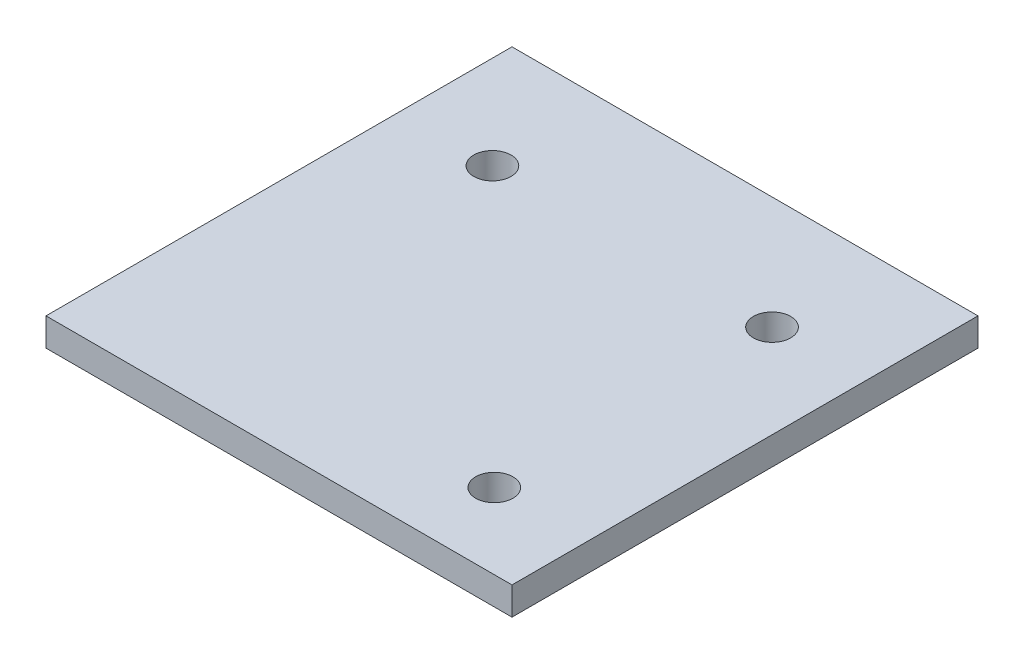
SolidWorks part; units mm, degrees
ref_plane "前视基准面" through (0, 0, 0) normal (0, 0, 1) x (1, 0, 0)
ref_plane "上视基准面" through (0, 0, 0) normal (0, 1, 0) x (1, 0, 0)
ref_plane "右视基准面" through (0, 0, 0) normal (1, 0, 0) x (0, 0, -1)
sketch "草图1" plane through (0, 0, 0) normal (0, 1, 0) x (1, 0, 0)
  line L1 (-25, -25) -> (25, -25)
  line L2 (-25, -25) -> (-25, 25)
  line L3 (-25, 25) -> (25, 25)
  line L4 (25, -25) -> (25, 25)
  line L5 (-25, -25) -> (25, 25) construction
  line L6 (-25, 25) -> (25, -25) construction
  point P0 (0, 0)
  dimension "D1" = 50
  dimension "D2" = 50
extrude "凸台-拉伸1" add sketch "草图1" along normal blind 3
sketch "草图2" plane through (0, 3, 0) normal (0, 1, 0) x (1, 0, 0)
  line L0 (-25, 12.9) -> (25, 12.9) construction
  line L1 (-25, 25) -> (-25, -25) construction
  line L2 (25, -25) -> (25, 25) construction
  line L3 (25, 25) -> (-25, 25) construction
  circle A0 centre (-15, 12.9) radius 2
  circle A1 centre (15, 12.9) radius 2
  dimension "D4" = 4
  dimension "D5" = 4
  dimension "D1" = 12.1
  dimension "D2" = 10
  dimension "D3" = 10
extrude "切除-拉伸1" cut sketch "草图2" against normal up to next
sketch "草图3" plane through (0, 3, 0) normal (0, 1, 0) x (1, 0, 0)
  line L0 (15, 12.9) -> (15, -25) construction
  line L1 (-25, -25) -> (25, -25) construction
  circle A0 centre (15, -16.9) radius 2
  dimension "D2" = 4
  dimension "D1" = 29.8
extrude "切除-拉伸2" cut sketch "草图3" against normal up to next
